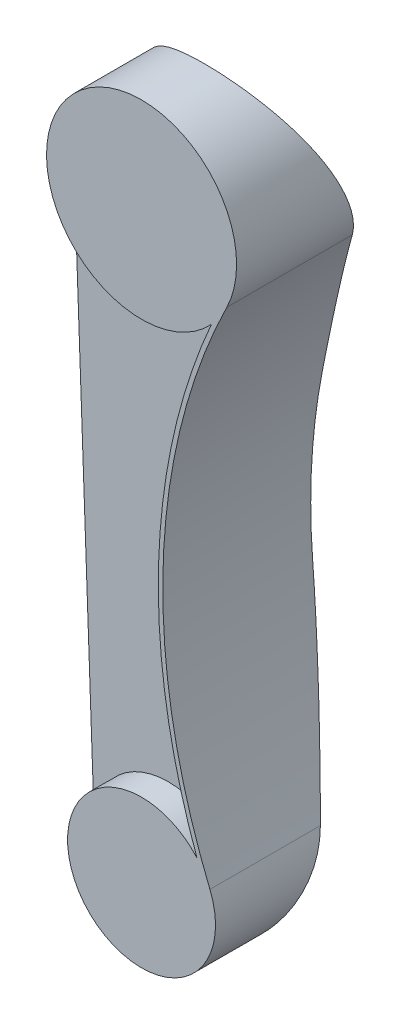
SolidWorks part; units mm, degrees
ref_plane "前基準面" through (0, 0, 0) normal (0, 0, 1) x (1, 0, 0)
ref_plane "上基準面" through (0, 0, 0) normal (0, 1, 0) x (1, 0, 0)
ref_plane "右基準面" through (0, 0, 0) normal (1, 0, 0) x (0, 0, -1)
sketch "草圖1" plane through (0, 0, 0) normal (0, 0, 1) x (1, 0, 0)
  circle A0 centre (0, 0) radius 106
  dimension "D1" = 212
extrude "填料-伸長1" add sketch "草圖1" against normal blind 70
sketch "草圖2" plane through (0, 0, 0) normal (0, 0, 1) x (1, 0, 0)
  line L0 (0, 0) -> (0, -650) construction
  circle A0 centre (0, -650) radius 82.5
  dimension "D1" = 165
  dimension "D2" = 650
extrude "填料-伸長2" add sketch "草圖2" against normal blind 59.51 separate body
sketch "草圖5" plane through (0, 0, 0) normal (0, 0, 1) x (1, 0, 0)
  line L0 (-82.5, -650) -> (-106, 0) construction
  circle A0 centre (0, -650) radius 82.5 construction
  circle A1 centre (0, 0) radius 106 construction
  arc A2 (95.0956, -46.8277) -> (76.2524, -618.5068) centre (717.8827, -353.5055) ccw
  circle A3 centre (0, -650) radius 82.5 construction
  circle A4 centre (0, 0) radius 106 construction
  arc A5 (-82.5, -650) -> (76.2524, -618.5068) centre (0, -650) ccw
  arc A6 (95.0956, -46.8277) -> (-105.7233, -7.6546) centre (0, 0) ccw
  arc A8 (-82.4472, -652.9516) -> (-105.9292, -3.8723) centre (-859899.1933, -31434.0033) ccw construction
  dimension "D1" = 717.8827
extrude "伸長-薄件2" add sketch "草圖5" against normal blind 165 thin
ref_plane "平面1" through (0, 0, -29.755) normal (0, 0, 1) x (1, 0, 0)
sketch "草圖6" plane through (0, 0, -29.755) normal (0, 0, 1) x (1, 0, 0)
  line L0 (-82.5, -650) -> (-105.7233, -7.6546)
  arc A4 (77.908, -71.8773) -> (61.8646, -595.4196) centre (717.8827, -353.5055) ccw
  arc A5 (61.8646, -595.4196) -> (76.2524, -618.5068) centre (0, -650) ccw
  arc A6 (95.0956, -46.8277) -> (76.2524, -618.5068) centre (717.8827, -353.5055) ccw
  arc A7 (95.0956, -46.8277) -> (77.908, -71.8773) centre (0, 0) ccw
  arc A9 (-82.5, -650) -> (76.2524, -618.5068) centre (0, -650) ccw
  arc A10 (95.0956, -46.8277) -> (76.2524, -618.5068) centre (717.8827, -353.5055) ccw
  arc A11 (95.0956, -46.8277) -> (-105.7233, -7.6546) centre (0, 0) ccw
  dimension "D1" = 0
extrude "填料-伸長3" add sketch "草圖6" against normal up to surface (135.245 mm away) up to face at (-8.668, -321.5441, -165)
sketch "草圖7" plane through (0, 0, 0) normal (1, 0, 0) x (0, 0, -1)
  line L0 (165, -732.5) -> (59.51, -732.5)
  line L1 (0, -732.5) -> (165, -732.5) construction
  line L2 (165, -650) -> (165, -7.6546) construction
  line L3 (165, -732.5) -> (165, -407.5)
  line L4 (0, -567.5) -> (0, -732.5) construction
  line L5 (70, 106) -> (165, 106)
  line L6 (165, 106) -> (0, 106) construction
  line L7 (165, 106) -> (165, -219)
  line L8 (0, 106) -> (0, -106) construction
  arc A0 (59.51, -732.5) -> (165, -407.5) centre (-388.3849, -407.5) ccw
  arc A1 (70, 106) -> (165, -219) centre (-438.4211, -219) cw
  dimension "D1" = 59.51
  dimension "D2" = 325
  dimension "D3" = 70
  dimension "D4" = 325
extrude "除料-伸長1" cut sketch "草圖7" against normal through all both and the other way through all
ref_plane "平面2" through (-82.5, -650, -29.755) normal (0.0361, -0.9993, 0) x (-0.9993, -0.0361, 0)
